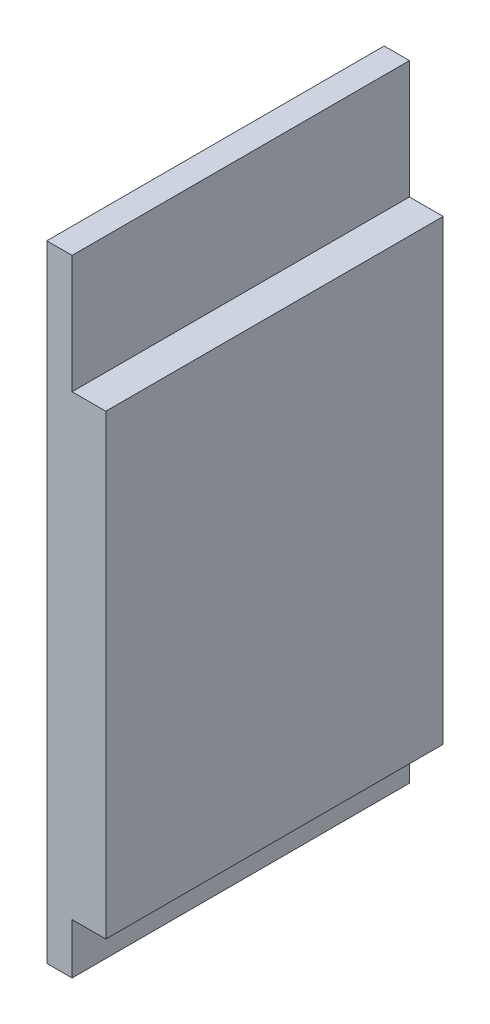
SolidWorks part; units mm, degrees
ref_plane "Front Plane" through (0, 0, 0) normal (0, 0, 1) x (1, 0, 0)
ref_plane "Top Plane" through (0, 0, 0) normal (0, 1, 0) x (1, 0, 0)
ref_plane "Right Plane" through (0, 0, 0) normal (1, 0, 0) x (0, 0, -1)
sketch "Sketch1" plane through (0, 0, 0) normal (0, 0, 1) x (1, 0, 0)
  line L0 (0, 18.8) -> (0, -18.8)
  line L1 (0, -18.8) -> (2, -18.8)
  line L2 (2, -18.8) -> (2, -15.8)
  line L3 (2, -15.8) -> (4, -15.8)
  line L4 (4, -15.8) -> (4, 11.8)
  line L5 (4, 11.8) -> (2, 11.8)
  line L6 (2, 11.8) -> (2, 18.8)
  line L7 (2, 18.8) -> (0, 18.8)
  line L8 (1.75, 18.55) -> (0.25, 18.55)
  line L9 (0.25, 18.55) -> (0.25, -18.55)
  line L10 (0.25, -18.55) -> (1.75, -18.55)
  line L11 (1.75, -18.55) -> (1.75, -15.55)
  line L12 (1.75, -15.55) -> (3.75, -15.55)
  line L13 (3.75, -15.55) -> (3.75, 11.55)
  line L14 (3.75, 11.55) -> (1.75, 11.55)
  line L15 (1.75, 11.55) -> (1.75, 18.55)
  dimension "D1" = 37.6
  dimension "D2" = 18.8
  dimension "D3" = 7
  dimension "D4" = 2
  dimension "D5" = 2
  dimension "D6" = 3
  dimension "D7" = 2
  dimension "D8" = 0.25
extrude "Boss-Extrude1" add sketch "Sketch1" along normal blind 20 contours L14 L15 L8 L9 L10 L11 L12 L13
